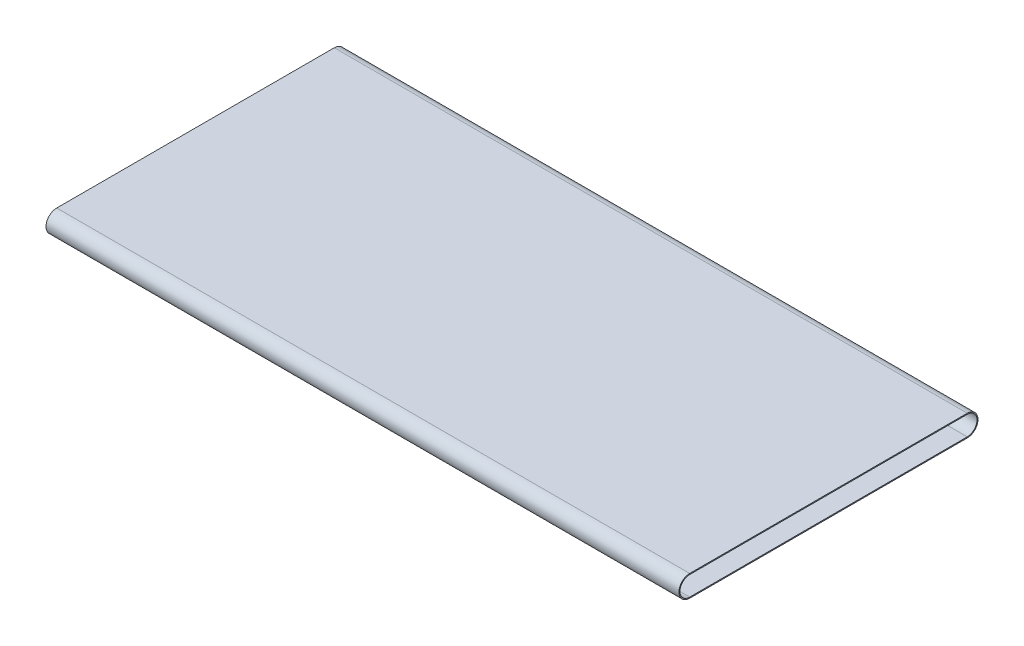
SolidWorks part; units mm, degrees
ref_plane "Front Plane" through (0, 0, 0) normal (0, 0, 1) x (1, 0, 0)
ref_plane "Top Plane" through (0, 0, 0) normal (0, 1, 0) x (1, 0, 0)
ref_plane "Right Plane" through (0, 0, 0) normal (1, 0, 0) x (0, 0, -1)
sketch "Sketch1" plane through (0, 0, 0) normal (1, 0, 0) x (0, 0, -1)
  line L0 (0, 0) -> (-1737.36, 0) construction
  line L1 (0, -67.31) -> (-1737.36, -67.31)
  line L2 (0, 67.31) -> (-1737.36, 67.31)
  line L3 (0, 0) -> (-1737.36, 0) construction
  line L4 (0, -60.96) -> (-1737.36, -60.96)
  line L5 (0, 60.96) -> (-1737.36, 60.96)
  arc A0 (0, -67.31) -> (0, 67.31) centre (0, 0) ccw
  arc A1 (-1737.36, 67.31) -> (-1737.36, -67.31) centre (-1737.36, 0) ccw
  arc A2 (0, -60.96) -> (0, 60.96) centre (0, 0) ccw
  arc A3 (-1737.36, 60.96) -> (-1737.36, -60.96) centre (-1737.36, 0) ccw
  point P3 (-868.68, 0)
  point P10 (-868.68, 0)
  dimension "D2" = 67.31
  dimension "D3" = 60.96
  dimension "D1" = 1737.36
extrude "Boss-Extrude1" add sketch "Sketch1" along normal blind 3962.4
